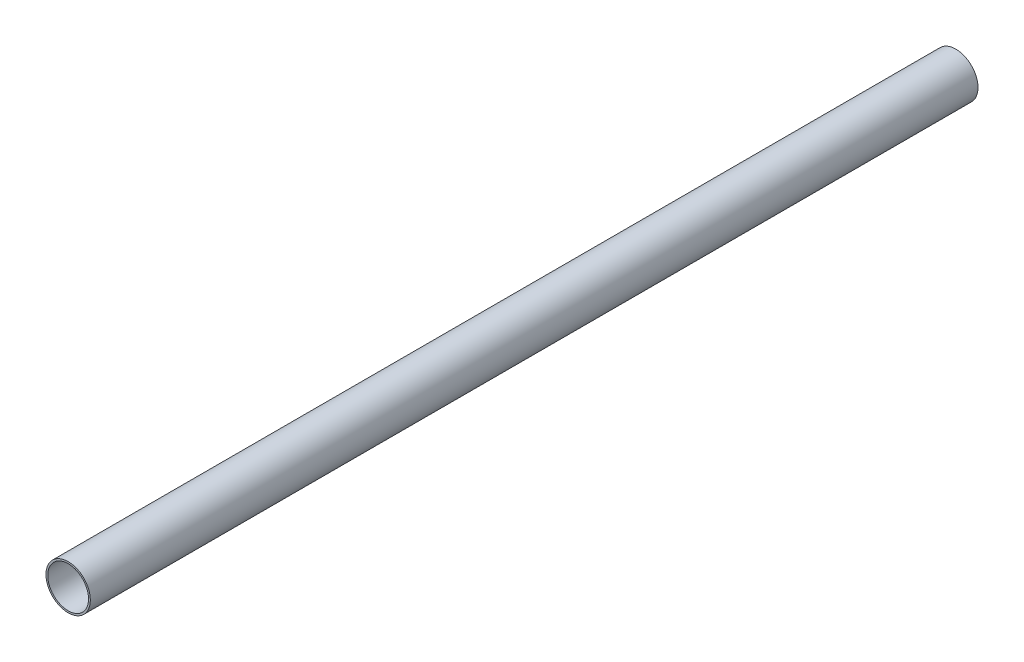
SolidWorks part; units mm, degrees
material "CF-ntbk"
ref_plane "Front Plane" through (0, 0, 0) normal (0, 0, 1) x (1, 0, 0)
ref_plane "Top Plane" through (0, 0, 0) normal (0, 1, 0) x (1, 0, 0)
ref_plane "Right Plane" through (0, 0, 0) normal (1, 0, 0) x (0, 0, -1)
sketch "Sketch1" plane through (0, 0, 0) normal (0, 0, 1) x (1, 0, 0)
  circle A0 centre (0, 0) radius 12.5
  circle A1 centre (0, 0) radius 11.5
  dimension "D1" = 25
  dimension "D2" = 23
extrude "Boss-Extrude1" add sketch "Sketch1" along normal mid plane 500
sketch "MountLine" plane through (0, 0, 0) normal (0, 1, 0) x (1, 0, 0)
  line L0 (-24.1369, 220) -> (21.9495, 220) construction
  line L1 (11.5, 250) -> (-11.5, 250) construction
  dimension "D1" = 30
equation "\"TubeOD\"=25"
equation "\"D1@Sketch1\"=\"TubeOD\""
equation "\"D2@Sketch1\"=\"TubeOD\"-2"
equation "\"TubeLength\"=500"
equation "\"D1@Boss-Extrude1\"=\"TubeLength\""
